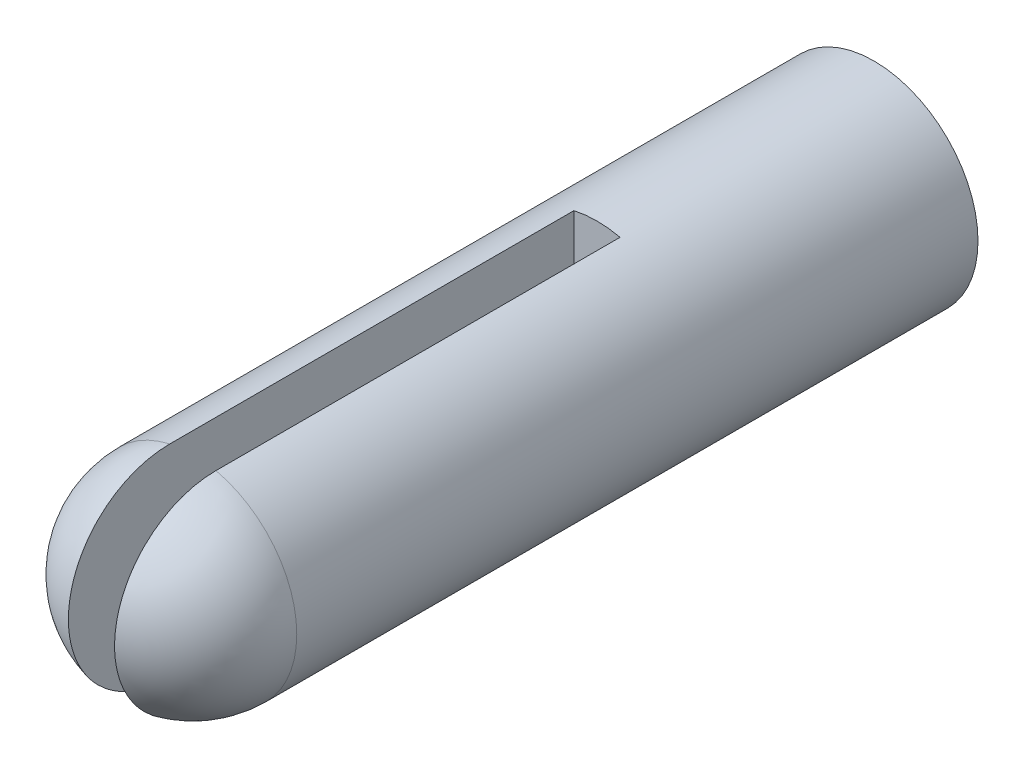
SolidWorks part; units mm, degrees
material "6061 Alloy"
ref_plane "Front Plane" through (0, 0, 0) normal (0, 0, 1) x (1, 0, 0)
ref_plane "Top Plane" through (0, 0, 0) normal (0, 1, 0) x (1, 0, 0)
ref_plane "Right Plane" through (0, 0, 0) normal (1, 0, 0) x (0, 0, -1)
sketch "Sketch1" plane through (0, 0, 0) normal (0, 0, 1) x (1, 0, 0)
  circle A0 centre (0, 0) radius 45
  dimension "D1" = 90
extrude "Boss-Extrude1" add sketch "Sketch1" along normal blind 340
fillet "Fillet1" radius 45 1 edges at (45, 0, 340)
sketch "Sketch2" plane through (0, 0, 0) normal (1, 0, 0) x (0, 0, -1)
  line L0 (-295, -45) -> (-295, 45) construction
  line L1 (30, -45) -> (-120, -45)
  line L2 (30, -45) -> (30, 45)
  line L3 (30, 45) -> (-120, 45)
  line L4 (-120, -45) -> (-120, 45)
  line L5 (-45, 45) -> (-45, -45) construction
  line L6 (30, 0) -> (-120, 0) construction
  point P0 (-45, 0)
  dimension "D3" = 250
  dimension "D1" = 150
  dimension "D2" = 90
extrude "Cut-Extrude1" cut sketch "Sketch2" against normal mid plane 20 flip side to cut
